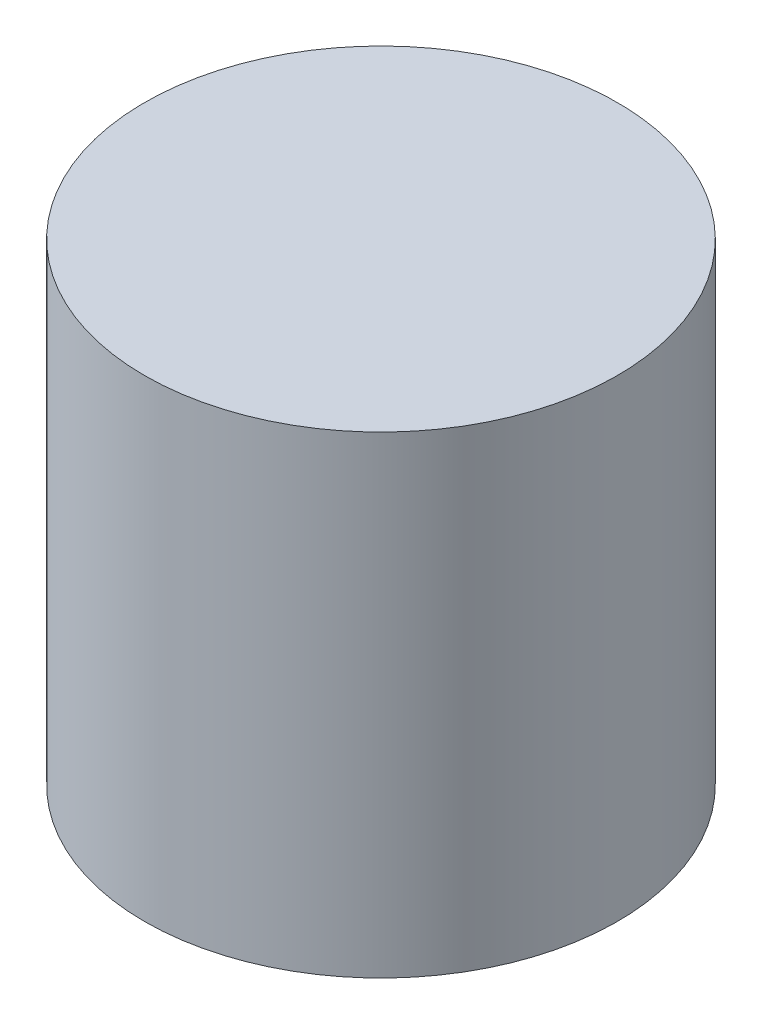
SolidWorks part; units mm, degrees
material "GREEN LIGHT"
ref_plane "Front Plane" through (0, 0, 0) normal (0, 0, 1) x (1, 0, 0)
ref_plane "Top Plane" through (0, 0, 0) normal (0, 1, 0) x (1, 0, 0)
ref_plane "Right Plane" through (0, 0, 0) normal (1, 0, 0) x (0, 0, -1)
sketch "Sketch1" plane through (0, 0, 0) normal (0, 1, 0) x (1, 0, 0)
  circle A0 centre (0, 0) radius 0.635
  dimension "D1" = 1.27
extrude "Boss-Extrude1" add sketch "Sketch1" along normal blind 1.27
